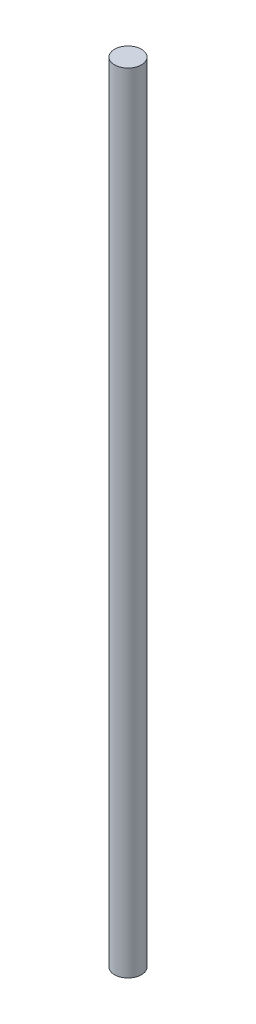
SolidWorks part; units mm, degrees
material "Plain Carbon Steel"
ref_plane "Front Plane" through (0, 0, 0) normal (0, 0, 1) x (1, 0, 0)
ref_plane "Top Plane" through (0, 0, 0) normal (0, 1, 0) x (1, 0, 0)
ref_plane "Right Plane" through (0, 0, 0) normal (1, 0, 0) x (0, 0, -1)
sketch "Sketch1" plane through (0, 0, 0) normal (0, 1, 0) x (1, 0, 0)
  circle A0 centre (0, 0) radius 6
  dimension "D1" = 12
extrude "Boss-Extrude1" add sketch "Sketch1" along normal blind 350
